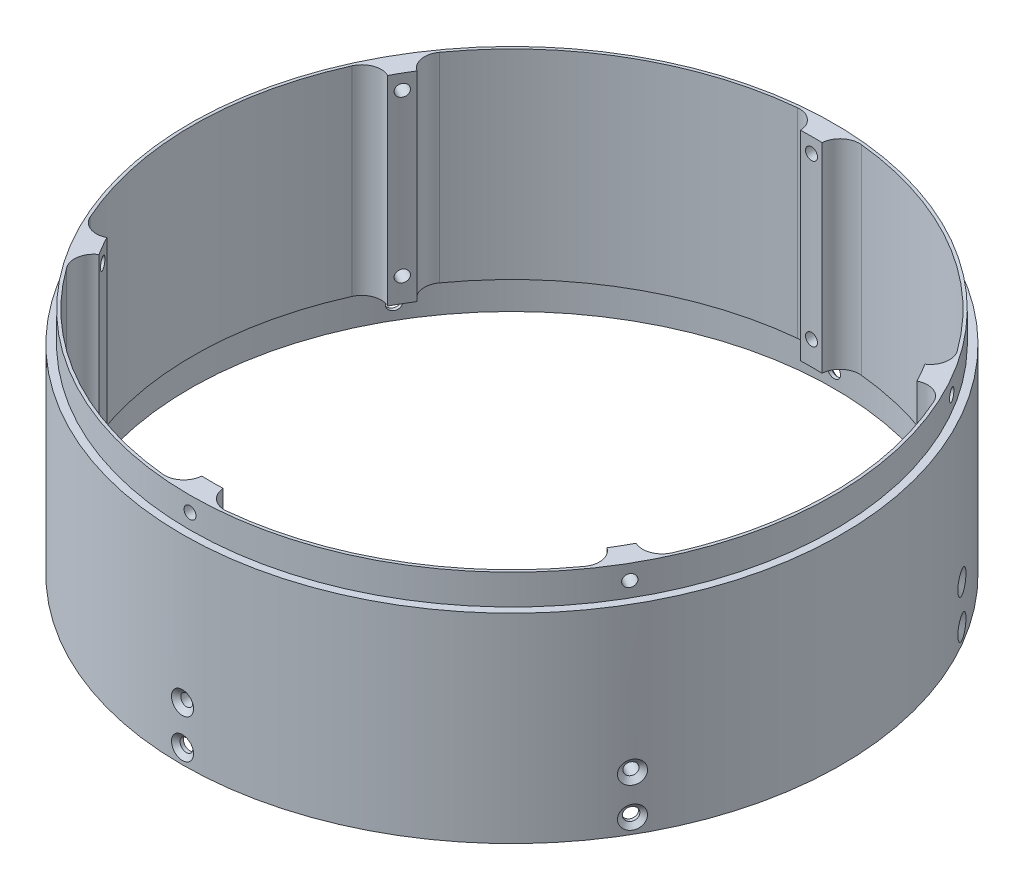
SolidWorks part; units mm, degrees
material "6061-T6 (SS)"
ref_plane "Front Plane" through (0, 0, 0) normal (0, 0, 1) x (1, 0, 0)
ref_plane "Top Plane" through (0, 0, 0) normal (0, 1, 0) x (1, 0, 0)
ref_plane "Right Plane" through (0, 0, 0) normal (1, 0, 0) x (0, 0, -1)
sketch "Sketch1" plane through (0, 0, 0) normal (0, 0, 1) x (1, 0, 0)
  line L0 (0, 42.3951) -> (0, -32.8937) construction
  line L1 (0, -60.071) -> (0, 60.071) construction
  line L2 (76.2, -50.8) -> (76.2, 0)
  line L3 (76.2, 0) -> (81.8896, 0)
  line L4 (81.8896, 0) -> (81.8896, -7.6708)
  line L5 (81.8896, -7.6708) -> (83.82, -7.6708)
  line L6 (83.82, -7.6708) -> (83.82, -58.42)
  line L7 (83.82, -58.42) -> (81.9404, -58.42)
  line L8 (81.9404, -58.42) -> (81.9404, -50.8)
  line L9 (81.9404, -50.8) -> (76.2, -50.8)
  line L10 (81.8896, -7.62) -> (84.2911, -7.62) construction
  dimension "D5" = 5.6896
  dimension "D10" = 76.2
  dimension "D2" = 7.62
  dimension "D4" = 7.62
  dimension "D6" = 7.62
revolve "Revolve1" add sketch "Sketch1" angle 360 about L0
sketch "Sketch2" plane through (0, 0, 0) normal (0, 1, 0) x (1, 0, 0)
  line L0 (0, 0) -> (0, 112.6688) construction
  line L1 (0, -60.071) -> (0, 60.071) construction
  line L2 (0, 0) -> (-128.6689, 74.287) construction
  line L3 (0, 0) -> (-50.2561, 87.0461) construction
  line L4 (0, 0) -> (-7.6343, 75.8166) construction
  arc A0 (-7.6343, 75.8166) -> (-61.8419, 44.5198) centre (0, 0) ccw construction
  arc A1 (-8.128, 80.7194) -> (-65.841, 47.3988) centre (0, 0) ccw
  arc A2 (-7.1406, 70.9138) -> (-57.8428, 41.6409) centre (0, 0) ccw
  arc A3 (-7.1406, 70.9138) -> (-8.128, 80.7194) centre (-7.6343, 75.8166) ccw
  arc A4 (-65.841, 47.3988) -> (-57.8428, 41.6409) centre (-61.8419, 44.5198) ccw
  circle A5 centre (0, 0) radius 81.8896 construction
  circle A7 centre (0, 0) radius 76.2 construction
  point P5 (-38.1, 65.9911)
  point P14 (-57.1427, 50.4098)
  point P19 (0, 0)
  point P20 (0, 0)
  dimension "D2" = 0.762
  dimension "D1" = 60
  dimension "D3" = 30
  dimension "D4" = 5.75
extrude "Cut-Extrude1" cut sketch "Sketch2" against normal through all
pattern_circular "CirPattern1" count 6 over 360 about axis through (0, 0, 0) along (0, 1, 0) of "Cut-Extrude1"
ref_plane "Plane1" through (0, 0, 83.82) normal (0, 0, 1) x (1, 0, 0)
hole_wizard "Tapped Hole for #4-40 Helicoil1" positions "Sketch3" profile "Sketch4" tap size "#4-40" standard "Helicoil® Inch"
sketch "Sketch3" plane through (0, 0, 83.82) normal (0, 0, 1) x (1, 0, 0)
  line L0 (81.8896, 0) -> (-81.8896, 0) construction
  line L1 (2.7181, 0) -> (-2.7181, 0) construction
  line L2 (2.7181, 0) -> (-2.7181, 0) construction
  line L3 (0, 0) -> (0, -3.81) construction
  line L5 (-2.7181, -50.8) -> (2.7181, -50.8) construction
  line L6 (-2.7181, -50.8) -> (2.7181, -50.8) construction
  line L7 (0, -50.8) -> (0, -44.704) construction
  point P0 (0, -3.81)
  point P20 (0, -44.704)
  dimension "D1" = 3.81
  dimension "D2" = 6.096
cosmetic thread "Hole Thread1" parameters "D1"=3.556, "D2"=3.7414
sketch "Sketch4" plane through (0, -3.81, 83.82) normal (1, 0, 0) x (0, -1, 0)
  line L0 (0, 0) -> (0, 26.3157)
  line L1 (0, 26.3157) -> (1.524, 25.4)
  line L2 (1.524, 25.4) -> (1.524, 1.1189)
  line L3 (1.524, 1.1189) -> (2.8575, 0)
  line L5 (2.8575, 0) -> (0, 0)
  line L6 (-1.524, 1.1189) -> (-2.8575, 0) construction
  line L10 (0, 26.3157) -> (-1.524, 25.4) construction
  line L11 (0, -6.35) -> (0, 107.95) construction
  dimension "Tap Drill Dia." = 3.048
  dimension "Tap Drill Depth" = 25.4
  dimension "Near C'Sink Dia." = 5.715
  dimension "Near C'Sink Angle" = 100
  dimension "Drill Angle" = 118
cosmetic thread "Hole Thread3" parameters "D1"=3.556, "D2"=3.7414
hole_wizard "CSK for #4 Flat Head Machine Screw (100)1" positions "Sketch5" profile "Sketch6" countersink size "#4" standard "ANSI Inch"
sketch "Sketch5" plane through (0, 0, 83.82) normal (0, 0, 1) x (1, 0, 0)
  line L0 (-2.7181, -50.8) -> (2.7181, -50.8) construction
  line L1 (-2.7181, -50.8) -> (2.7181, -50.8) construction
  line L2 (0, -50.8) -> (0, -54.61) construction
  point P0 (0, -54.61)
  point P19 (0, 0)
  dimension "D1" = 3.81
sketch "Sketch6" plane through (0, -54.61, 83.82) normal (1, 0, 0) x (0, -1, 0)
  line L0 (0, 0) -> (0, 26.3806)
  line L1 (0, 26.3806) -> (1.6319, 25.4)
  line L2 (1.6319, 25.4) -> (1.6319, 1.0284)
  line L3 (1.6319, 1.0284) -> (2.8575, 0)
  line L5 (2.8575, 0) -> (0, 0)
  line L6 (-1.6319, 1.0284) -> (-2.8575, 0) construction
  line L10 (0, 26.3806) -> (-1.632, 25.4) construction
  line L11 (0, -6.35) -> (0, 107.95) construction
  dimension "Hole Dia." = 3.2639
  dimension "Hole Depth" = 25.4
  dimension "Near C'Sink Dia." = 5.715
  dimension "Near C'Sink Angle" = 100
  dimension "Drill Angle" = 118
pattern_circular "CirPattern2" count 6 over 360 about axis through (0, 42.3951, 0) along (0, 1, 0) of "Tapped Hole for #4-40 Helicoil1", "CSK for #4 Flat Head Machine Screw (100)1"
equation "\"nominalLength\"= 2"
equation "\"D8@Sketch1\"=\"nominalLength\""
